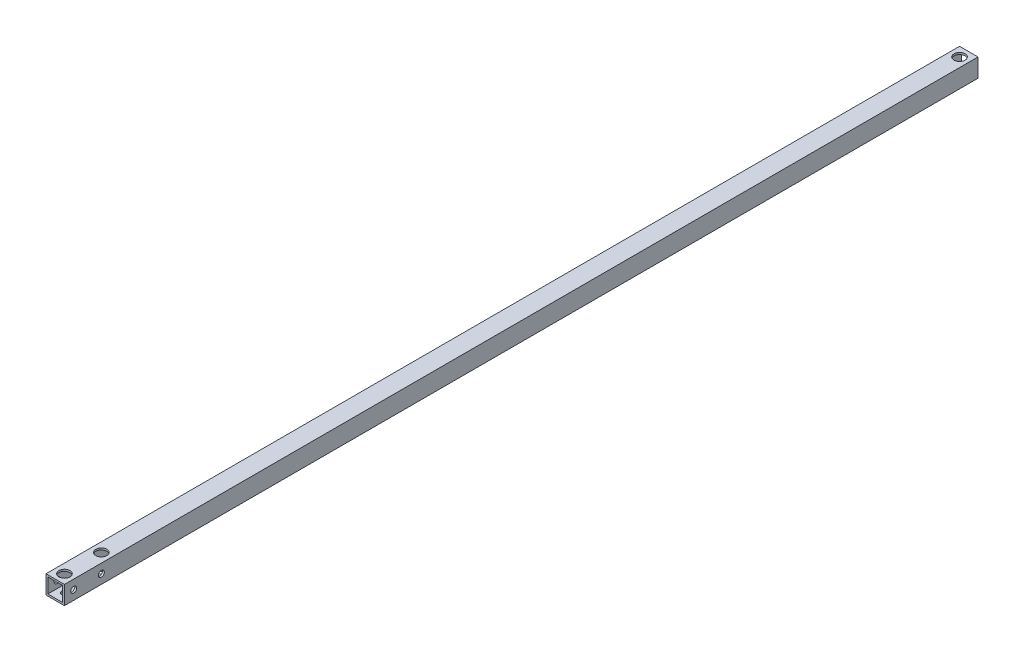
SolidWorks part; units mm, degrees
material "1060 合金"
ref_plane "正面" through (0, 0, 0) normal (0, 0, 1) x (1, 0, 0)
ref_plane "平面" through (0, 0, 0) normal (0, 1, 0) x (1, 0, 0)
ref_plane "右側面" through (0, 0, 0) normal (1, 0, 0) x (0, 0, -1)
sketch "ｽｹｯﾁ1" plane through (0, 0, 0) normal (0, 0, 1) x (1, 0, 0)
  line L1 (5, 5) -> (-5, 5)
  line L2 (5, 5) -> (5, -5)
  line L3 (5, -5) -> (-5, -5)
  line L4 (-5, 5) -> (-5, -5)
  line L5 (5, 5) -> (-5, -5) construction
  line L6 (5, -5) -> (-5, 5) construction
  point P0 (0, 0)
  dimension "D1" = 10
extrude "押し出し-薄板1" add sketch "ｽｹｯﾁ1" along normal blind 495 thin thin type one direction reverse wall 1
sketch "ｽｹｯﾁ2" plane through (0, 5, 0) normal (0, 1, 0) x (1, 0, 0)
  line L0 (0, 0) -> (0, -495) construction
  line L1 (5, -495) -> (-5, -495) construction
  line L2 (5, 0) -> (-5, 0) construction
  line L3 (0, -247.5) -> (5, -247.5) construction
  line L4 (5, -495) -> (5, 0) construction
  circle A0 centre (0, -5) radius 1.6
  circle A2 centre (0, -490) radius 1.6
  circle A4 centre (0, -470) radius 1.6
  dimension "D1" = 5
  dimension "D2" = 3.2
  dimension "D3" = 5
  dimension "D4" = 3.2
  dimension "D5" = 3.2
  dimension "D6" = 20
extrude "ｶｯﾄ - 押し出し1" cut sketch "ｽｹｯﾁ2" against normal through all
sketch "ｽｹｯﾁ3" plane through (0, 5, 0) normal (0, 1, 0) x (1, 0, 0)
  line L0 (0, -495) -> (0, 0) construction
  line L1 (5, -495) -> (-5, -495) construction
  line L2 (0, -247.5) -> (5, -247.5) construction
  line L3 (5, -495) -> (5, 0) construction
  circle A0 centre (0, -5) radius 3
  circle A2 centre (0, -490) radius 3
  circle A3 centre (0, -470) radius 3
  dimension "D1" = 6
  dimension "D2" = 6
  dimension "D3" = 6
extrude "ｶｯﾄ - 押し出し2" cut sketch "ｽｹｯﾁ3" against normal up to next
sketch "ｽｹｯﾁ8" plane through (5, 0, 0) normal (1, 0, 0) x (0, 0, -1)
  line L0 (-495, 0) -> (0, 0) construction
  line L1 (-495, -5) -> (-495, 5) construction
  circle A0 centre (-490, 0) radius 1.6
  circle A1 centre (-475, 0) radius 1.6
  dimension "D1" = 3.2
  dimension "D2" = 3.2
  dimension "D3" = 15
  dimension "D4" = 5
extrude "ｶｯﾄ - 押し出し7" cut sketch "ｽｹｯﾁ8" against normal through all
